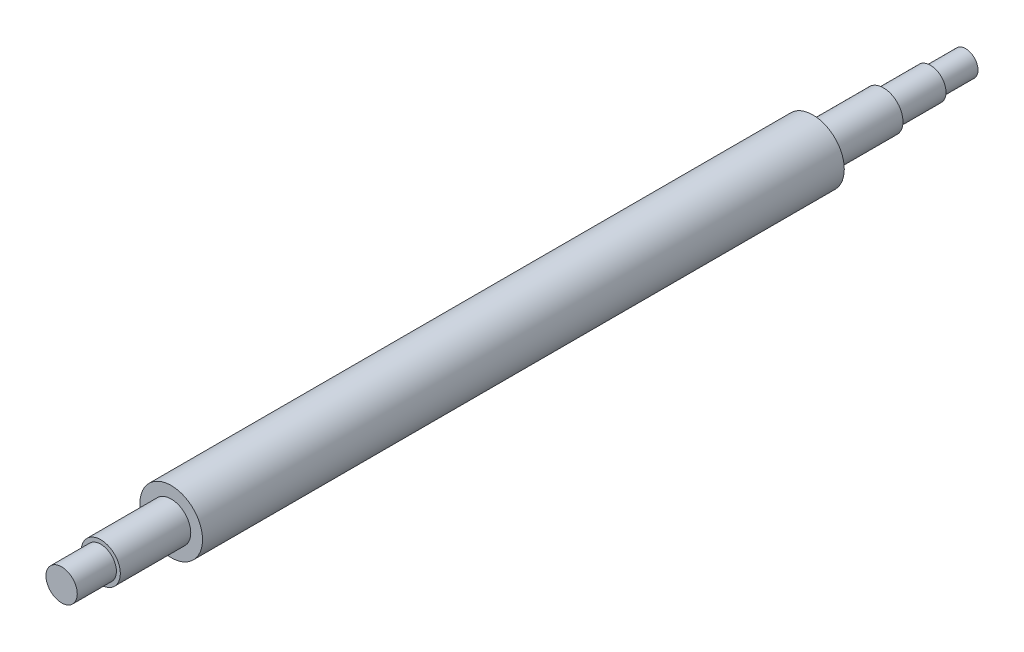
SolidWorks part; units mm, degrees
ref_plane "前视基准面" through (0, 0, 0) normal (0, 0, 1) x (1, 0, 0)
ref_plane "上视基准面" through (0, 0, 0) normal (0, 1, 0) x (1, 0, 0)
ref_plane "右视基准面" through (0, 0, 0) normal (1, 0, 0) x (0, 0, -1)
sketch "草图1" plane through (0, 0, 0) normal (0, 0, 1) x (1, 0, 0)
  circle A0 centre (0, 0) radius 8
  dimension "D1" = 16
extrude "凸台-拉伸1" add sketch "草图1" along normal blind 164
cosmetic thread "装饰螺纹线1" parameters "D2"=15.999
sketch "草图2" plane through (0, 0, 164) normal (0, 0, 1) x (1, 0, 0)
  circle A0 centre (0, 0) radius 5
  dimension "D1" = 10
extrude "凸台-拉伸2" add sketch "草图2" along normal blind 18 separate body
sketch "草图4" plane through (0, 0, 0) normal (0, 0, -1) x (-1, 0, 0)
  circle A0 centre (0, 0) radius 5
  dimension "D1" = 10
extrude "凸台-拉伸3" add sketch "草图4" along normal blind 18 separate body
sketch "草图5" plane through (0, 0, 182) normal (0, 0, 1) x (1, 0, 0)
  circle A0 centre (0, 0) radius 4
  dimension "D1" = 8
extrude "凸台-拉伸4" add sketch "草图5" along normal blind 10
sketch "草图9" plane through (0, 0, -18) normal (0, 0, -1) x (-1, 0, 0)
  circle A0 centre (0, 0) radius 4
extrude "凸台-拉伸5" add sketch "草图9" along normal blind 12
sketch "草图10" plane through (0, 0, -30) normal (0, 0, -1) x (-1, 0, 0)
  circle A2 centre (0, 0) radius 3.175
extrude "凸台-拉伸6" add sketch "草图10" along normal blind 9
